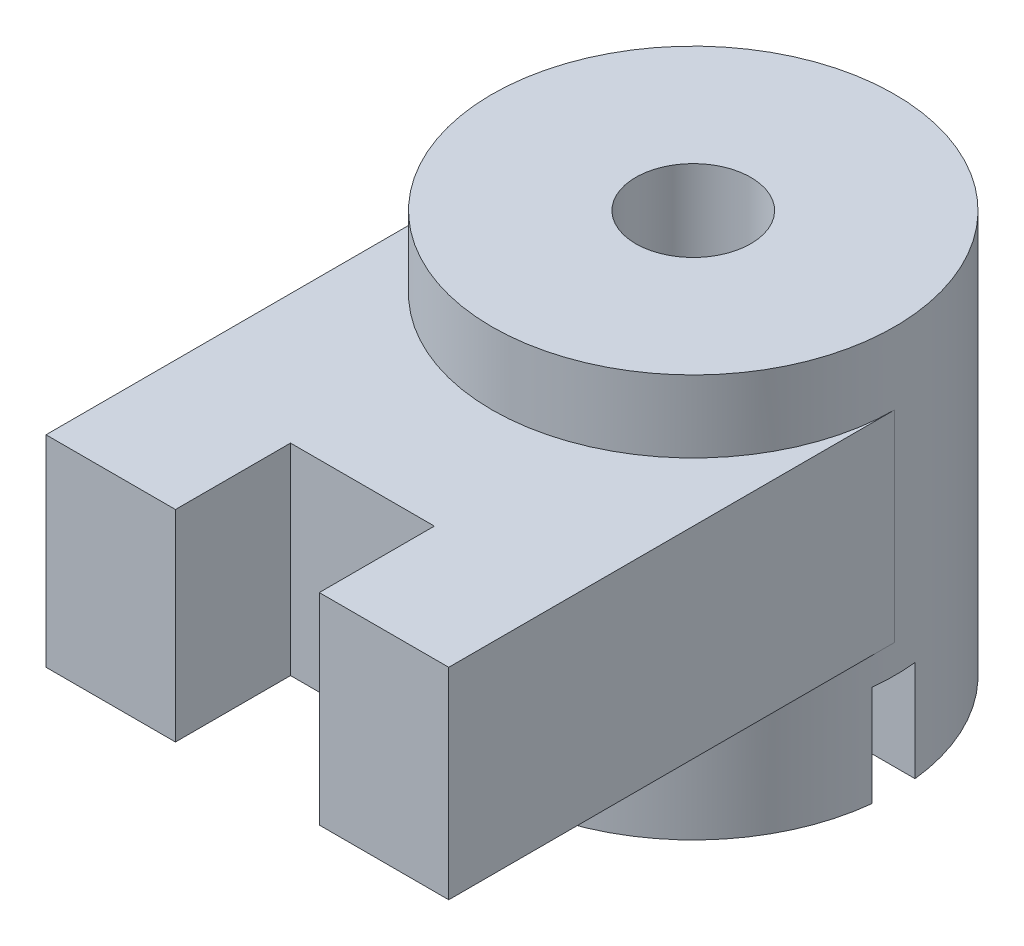
SolidWorks part; units mm, degrees
ref_plane "Plan de face" through (0, 0, 0) normal (0, 0, 1) x (1, 0, 0)
ref_plane "Plan de dessus" through (0, 0, 0) normal (0, 1, 0) x (1, 0, 0)
ref_plane "Plan de droite" through (0, 0, 0) normal (1, 0, 0) x (0, 0, -1)
sketch "Esquisse2" plane through (0, 0, 0) normal (0, 1, 0) x (1, 0, 0)
  circle A0 centre (0, 0) radius 20
  circle A1 centre (0, 0) radius 70
  dimension "D1" = 40
  dimension "D2" = 140
extrude "Boss.-Extru.1" add sketch "Esquisse2" along normal blind 140
sketch "Esquisse3" plane through (0, 0, 0) normal (1, 0, 0) x (0, 0, -1)
  line L0 (-70, 0) -> (70, 0) construction
  line L1 (-70, 0) -> (70, 0) construction
  line L3 (-7.5, -35) -> (7.5, -35)
  line L4 (-7.5, -35) -> (-7.5, 35)
  line L5 (-7.5, 35) -> (7.5, 35)
  line L6 (7.5, -35) -> (7.5, 35)
  line L7 (-7.5, -35) -> (7.5, 35) construction
  line L8 (-7.5, 35) -> (7.5, -35) construction
  point P6 (0, 0)
  dimension "D1" = 15
  dimension "D2" = 70
extrude "Enlèv. mat.-Extru.1" cut sketch "Esquisse3" against normal through all both and the other way through all
sketch "Esquisse7" plane through (0, 0, 0) normal (1, 0, 0) x (0, 0, -1)
  line L0 (-70, 140) -> (-70, 0) construction
  line L3 (-155, 45) -> (-155, 115)
  line L9 (-155, 45) -> (-155, 115)
  line L12 (-155, 115) -> (0, 115)
  line L13 (-155, 115) -> (-155, 45)
  line L14 (-155, 45) -> (0, 45)
  line L15 (0, 115) -> (0, 45)
  point P4 (-70, 70)
  dimension "D2" = 70
  dimension "D4" = 155
extrude "Boss.-Extru.3" add sketch "Esquisse7" along normal mid plane 140
sketch "Esquisse11" plane through (0, 115, 0) normal (0, 1, 0) x (1, 0, 0)
  line L0 (70, -155) -> (-70, -155) construction
  line L1 (-25, -195) -> (25, -195)
  line L2 (-25, -195) -> (-25, -115)
  line L3 (-25, -115) -> (25, -115)
  line L4 (25, -195) -> (25, -115)
  line L5 (-25, -195) -> (25, -115) construction
  line L6 (-25, -115) -> (25, -195) construction
  point P0 (0, -155)
  dimension "D1" = 50
  dimension "D2" = 80
extrude "Enlèv. mat.-Extru.5" cut sketch "Esquisse11" against normal through all both and the other way through all
sketch "Esquisse10" plane through (0, 140, 0) normal (0, 1, 0) x (1, 0, 0)
  circle A0 centre (0, 0) radius 20
extrude "Enlèv. mat.-Extru.4" cut sketch "Esquisse10" against normal mid plane 360
